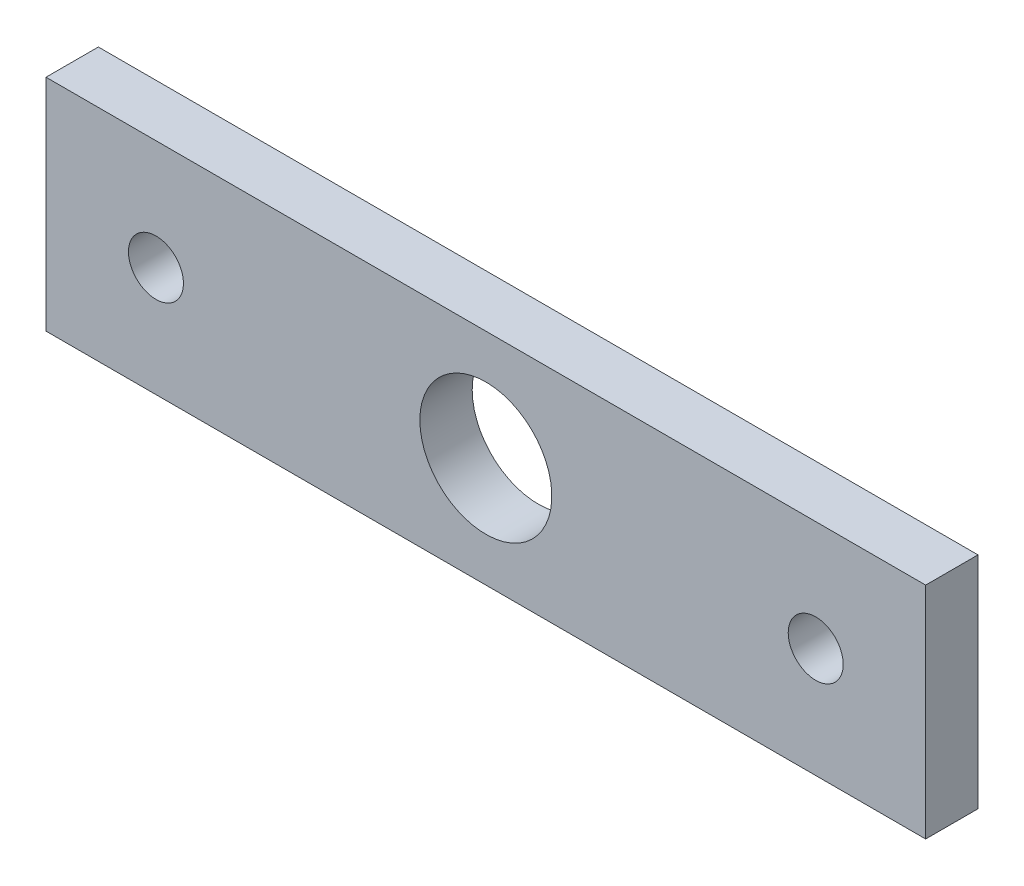
SolidWorks part; units mm, degrees
material "6061-T4 (SS)"
ref_plane "Front Plane" through (0, 0, 0) normal (0, 0, 1) x (1, 0, 0)
ref_plane "Top Plane" through (0, 0, 0) normal (0, 1, 0) x (1, 0, 0)
ref_plane "Right Plane" through (0, 0, 0) normal (1, 0, 0) x (0, 0, -1)
ref_plane "Plane1" through (0, 0, 4.76) normal (0, 0, 1) x (1, 0, 0)
sketch "Sketch1" plane through (0, 0, 4.76) normal (0, 0, 1) x (1, 0, 0)
  line L0 (80, 20) -> (0, 20)
  line L1 (0, 20) -> (0, 0)
  line L2 (0, 0) -> (80, 0)
  line L3 (80, 0) -> (80, 20)
  circle A0 centre (10, 10) radius 2.5
  circle A1 centre (70, 10) radius 2.5
  circle A2 centre (40, 10) radius 6
extrude "Boss-Extrude1" add sketch "Sketch1" against normal blind 4.76
